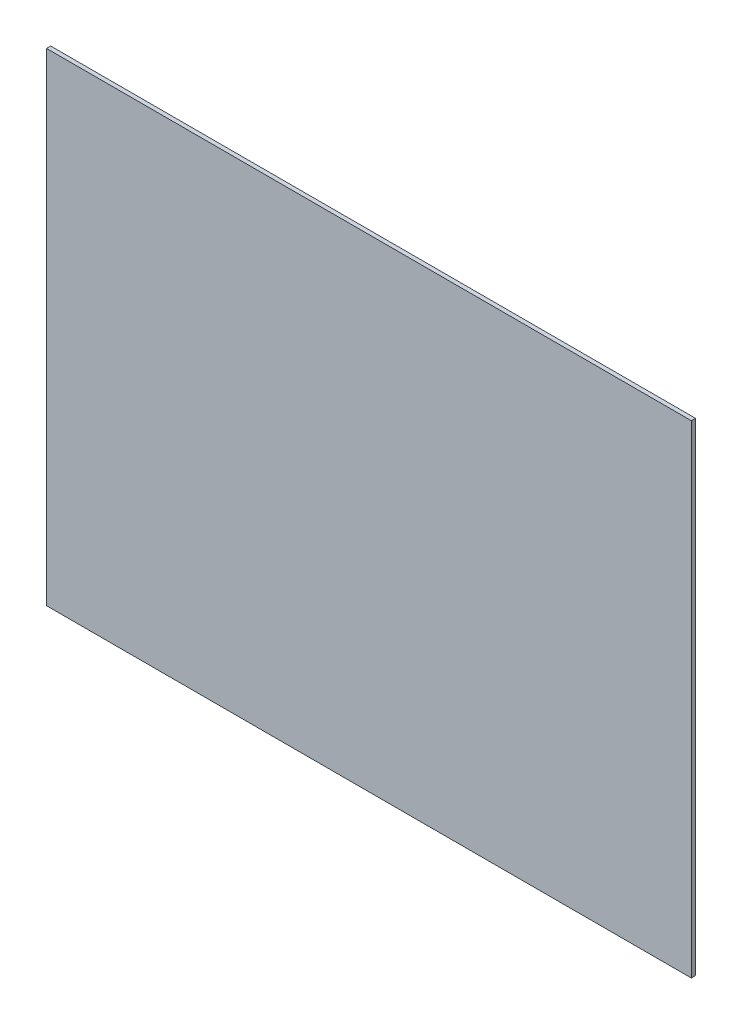
SolidWorks part; units mm, degrees
ref_plane "Front Plane" through (0, 0, 0) normal (0, 0, 1) x (1, 0, 0)
ref_plane "Top Plane" through (0, 0, 0) normal (0, 1, 0) x (1, 0, 0)
ref_plane "Right Plane" through (0, 0, 0) normal (1, 0, 0) x (0, 0, -1)
sketch "Sketch1" plane through (0, 0, 0) normal (0, 0, 1) x (1, 0, 0)
  line L1 (-165.71, 124.04) -> (165.71, 124.04)
  line L2 (-165.71, 124.04) -> (-165.71, -124.04)
  line L3 (-165.71, -124.04) -> (165.71, -124.04)
  line L4 (165.71, 124.04) -> (165.71, -124.04)
  line L5 (-165.71, 124.04) -> (165.71, -124.04) construction
  line L6 (-165.71, -124.04) -> (165.71, 124.04) construction
  point P0 (0, 0)
  dimension "D1" = 331.42
  dimension "D2" = 248.08
extrude "Boss-Extrude1" add sketch "Sketch1" along normal blind 2.14
